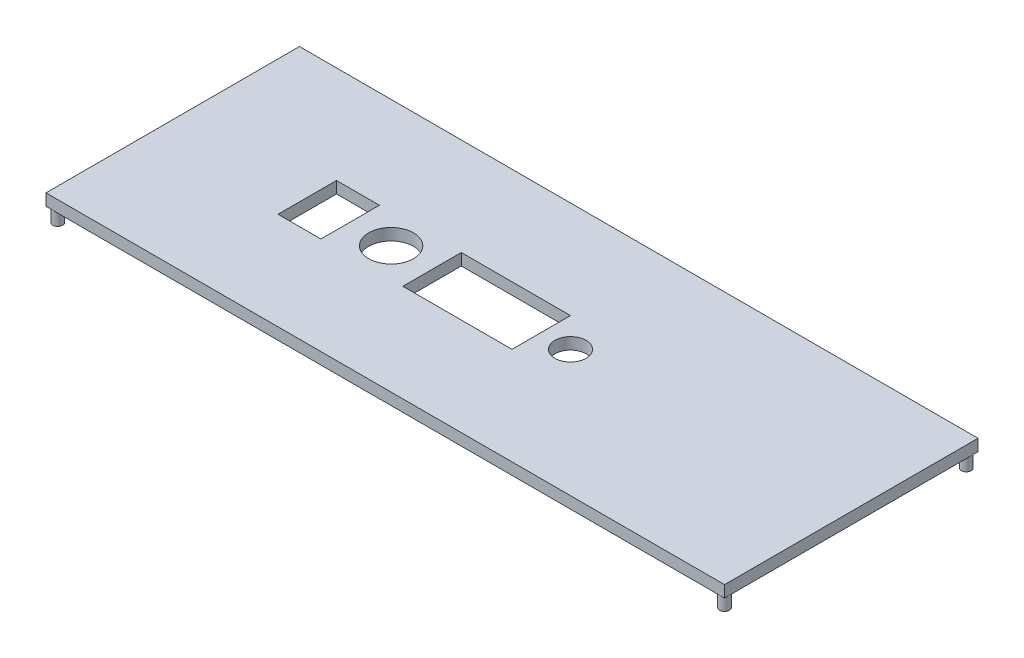
SolidWorks part; units mm, degrees
ref_plane "Front Plane" through (0, 0, 0) normal (0, 0, 1) x (1, 0, 0)
ref_plane "Top Plane" through (0, 0, 0) normal (0, 1, 0) x (1, 0, 0)
ref_plane "Right Plane" through (0, 0, 0) normal (1, 0, 0) x (0, 0, -1)
sketch "Sketch1" plane through (0, 0, 0) normal (0, 1, 0) x (1, 0, 0)
  line L1 (-64.0246, 34.3099) -> (109.9754, 34.3099)
  line L2 (-64.0246, 34.3099) -> (-64.0246, -30.6901)
  line L3 (-64.0246, -30.6901) -> (109.9754, -30.6901)
  line L4 (109.9754, 34.3099) -> (109.9754, -30.6901)
  dimension "D1" = 174
  dimension "D2" = 65
extrude "Boss-Extrude1" add sketch "Sketch1" along normal blind 3
sketch "Sketch2" plane through (0, 3, 0) normal (0, 1, 0) x (1, 0, 0)
  line L0 (109.9754, 34.3099) -> (-64.0246, 34.3099) construction
  line L1 (109.9754, -30.6901) -> (109.9754, 34.3099) construction
  line L3 (2.4754, -5.6901) -> (30.4754, -5.6901)
  line L4 (2.4754, -5.6901) -> (2.4754, 9.3099)
  line L5 (2.4754, 9.3099) -> (30.4754, 9.3099)
  line L6 (30.4754, -5.6901) -> (30.4754, 9.3099)
  line L7 (2.4754, -5.6901) -> (30.4754, 9.3099) construction
  line L8 (2.4754, 9.3099) -> (30.4754, -5.6901) construction
  line L9 (-29.5246, -5.6901) -> (-18.5246, -5.6901)
  line L10 (-29.5246, -5.6901) -> (-29.5246, 9.3099)
  line L11 (-29.5246, 9.3099) -> (-18.5246, 9.3099)
  line L12 (-18.5246, -5.6901) -> (-18.5246, 9.3099)
  line L13 (-29.5246, -5.6901) -> (-18.5246, 9.3099) construction
  line L14 (-29.5246, 9.3099) -> (-18.5246, -5.6901) construction
  circle A0 centre (37.9754, 1.8099) radius 4
  circle A1 centre (-8.0246, 1.8099) radius 5.75
  point P6 (16.4754, 1.8099)
  point P14 (-24.0246, 1.8099)
  dimension "D1" = 8
  dimension "D8" = 11.5
  dimension "D2" = 32.5
  dimension "D3" = 72
  dimension "D4" = 28
  dimension "D5" = 15
  dimension "D6" = 93.5
  dimension "D7" = 32.5
  dimension "D9" = 32.5
  dimension "D10" = 118
  dimension "D11" = 11
  dimension "D12" = 15
  dimension "D13" = 32.5
  dimension "D14" = 134
extrude "Cut-Extrude1" cut sketch "Sketch2" against normal blind 3
sketch "Sketch3" plane through (0, 0, 0) normal (0, -1, 0) x (1, 0, 0)
  line L0 (-64.0246, -34.3099) -> (-64.0246, 30.6901) construction
  line L1 (109.9754, -34.3099) -> (-64.0246, -34.3099) construction
  circle A0 centre (-62.4346, -32.7199) radius 1.25
  dimension "D1" = 2.5
  dimension "D2" = 1.59
  dimension "D3" = 1.59
extrude "Boss-Extrude2" add sketch "Sketch3" along normal blind 3.5
pattern_linear "LPattern1" count 2 spacing 171 along (1, 0, 0) count 2 spacing 62 along (0, 0, 1) of "Boss-Extrude2"
